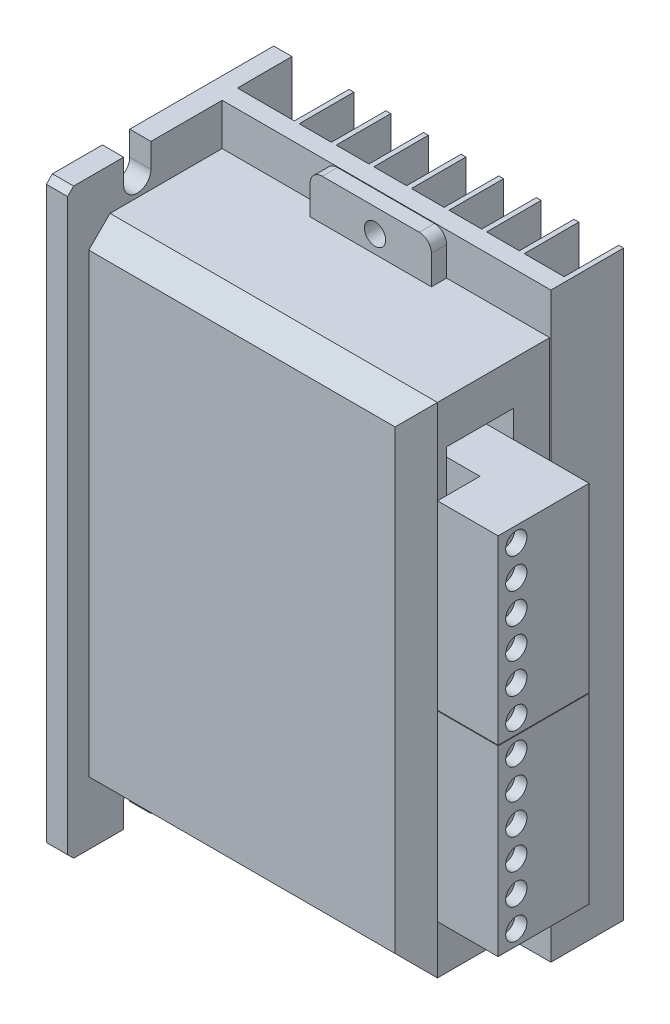
SolidWorks part; units mm, degrees
material "1060 Сплав"
ref_plane "Спереди" through (0, 0, 0) normal (0, 0, 1) x (1, 0, 0)
ref_plane "Сверху" through (0, 0, 0) normal (0, 1, 0) x (1, 0, 0)
ref_plane "Справа" through (0, 0, 0) normal (1, 0, 0) x (0, 0, -1)
sketch "Эскиз1" plane through (0, 0, 0) normal (0, 0, 1) x (1, 0, 0)
  line L0 (0, 0) -> (-27, 0) construction
  line L1 (-27, -41.1) -> (27, -41.1)
  line L2 (-27, -41.1) -> (-27, 41.1)
  line L3 (-27, 41.1) -> (27, 41.1)
  line L4 (27, -41.1) -> (27, 41.1)
  line L5 (-27, -41.1) -> (27, 41.1) construction
  line L6 (-27, 41.1) -> (27, -41.1) construction
  point P0 (0, 0)
  dimension "D1" = 82.2
  dimension "D2" = 54
extrude "Бобышка-Вытянуть1" add sketch "Эскиз1" along normal blind 22
chamfer "Фаска1" distance 3.5 angle 45 3 edges at (0, -41.1, 22) (27, 0, 22) (0, 41.1, 22)
sketch "Эскиз2" plane through (0, 0, 0) normal (0, 0, -1) x (-1, 0, 0)
  line L1 (-27.2, -48) -> (27, -48)
  line L2 (-27.2, -48) -> (-27.2, 48)
  line L3 (-27.2, 48) -> (27, 48)
  line L4 (27, -48) -> (27, 48)
  line L5 (27, 41.1) -> (27, -41.1) construction
  line L6 (27, 0) -> (0, 0) construction
  dimension "D1" = 96
  dimension "D3" = 54.2
extrude "Бобышка-Вытянуть2" add sketch "Эскиз2" along normal blind 12
sketch "Эскиз3" plane through (-27, 0, 0) normal (-1, 0, 0) x (0, 0, 1)
  line L1 (-12, 48) -> (11.75, 48)
  line L2 (-12, 48) -> (-12, -48)
  line L3 (-12, -48) -> (11.75, -48)
  line L4 (25.5, 48) -> (25.5, -48)
  line L6 (22, 37.6) -> (22, -37.6) construction
  line L7 (14, 59) -> (14, -59) construction
  line L8 (-12, 0) -> (25.5, 0) construction
  line L9 (11.75, 44) -> (11.75, 48)
  line L10 (16.25, 44) -> (16.25, 48)
  line L11 (16.25, 48) -> (25.5, 48)
  line L12 (16.25, -44) -> (16.25, -48)
  line L13 (11.75, -44) -> (11.75, -48)
  line L14 (16.25, -48) -> (25.5, -48)
  arc A0 (11.75, 44) -> (16.25, 44) centre (14, 44) ccw
  arc A1 (11.75, -44) -> (16.25, -44) centre (14, -44) cw
  dimension "D3" = 4.5
  dimension "D4" = 44
  dimension "D1" = 3.5
  dimension "D2" = 11.5
extrude "Бобышка-Вытянуть3" add sketch "Эскиз3" along normal blind 3.5
chamfer "Фаска2" distance 1 angle 45 2 edges at (-28.75, -48, 25.5) (-28.75, 48, 25.5)
sketch "Эскиз5" plane through (0, 0, -12) normal (0, 0, -1) x (-1, 0, 0)
  line L0 (30.5, 48) -> (-27.2, 48) construction
  line L1 (27.5, 48) -> (18.1, 48)
  line L2 (27.5, 48) -> (27.5, -48)
  line L3 (27.5, -48) -> (18.1, -48)
  line L4 (18.1, 48) -> (18.1, -48)
  line L5 (-27.2, -48) -> (30.5, -48) construction
  line L6 (30.5, 48) -> (30.5, -48) construction
  line L9 (17.3, 48) -> (17.3, -48)
  line L11 (12, 48) -> (12, -48)
  line L70 (17.3, 48) -> (12, 48)
  line L76 (12, -48) -> (17.3, -48)
  line L77 (11.2, 48) -> (11.2, -48)
  line L78 (5.8, 48) -> (5.8, -48)
  line L79 (5.8, 48) -> (11.2, 48)
  line L81 (5.8, 48) -> (5.8, -48)
  line L83 (5, 48) -> (5, -48)
  line L84 (5.8, -48) -> (11.2, -48)
  line L85 (-0.4, 48) -> (-0.4, -48)
  line L86 (5, 48) -> (5, -48)
  line L87 (-0.4, -48) -> (5, -48)
  line L88 (5.8, 48) -> (5.8, -48)
  line L89 (-6.6, 48) -> (-6.6, -48)
  line L90 (-1.2, 48) -> (-1.2, -48)
  line L91 (-6.6, -48) -> (-1.2, -48)
  line L92 (-0.4, 48) -> (-0.4, -48)
  line L93 (-12.8, 48) -> (-12.8, -48)
  line L94 (-7.4, 48) -> (-7.4, -48)
  line L95 (-12.8, -48) -> (-7.4, -48)
  line L96 (-6.6, 48) -> (-6.6, -48)
  line L97 (-19, 48) -> (-19, -48)
  line L98 (-13.6, 48) -> (-13.6, -48)
  line L99 (-19, -48) -> (-13.6, -48)
  line L100 (-12.8, 48) -> (-12.8, -48)
  line L102 (-19.8, 48) -> (-19.8, -48)
  line L103 (-25.2, -48) -> (-19.8, -48)
  line L104 (-19, 48) -> (-19, -48)
  line L105 (5, 48) -> (-0.4, 48)
  line L106 (-1.2, 48) -> (-6.6, 48)
  line L107 (-7.4, 48) -> (-12.8, 48)
  line L108 (-13.6, 48) -> (-19, 48)
  line L109 (-19.8, 48) -> (-25.2, 48)
  line L110 (5, 48) -> (-0.4, 48)
  line L111 (5.8, -48) -> (11.2, -48)
  line L112 (5, -48) -> (-0.4, -48)
  line L113 (-25.2, 48) -> (-26.3933, 48)
  line L114 (-25.2, 48) -> (-25.2, -48) [skipped]
  line L115 (-26.3933, 48) -> (-26.3933, -48)
  line L116 (-26.3933, -48) -> (-25.2, -48)
  line L117 (-27.2, 48) -> (-27.2, -48) construction
  line L119 (-0.4, 48) -> (5, 48)
  line L120 (-0.4, 48) -> (-0.4, -48)
  line L121 (-0.4, -48) -> (5, -48)
  line L122 (5, 48) -> (5, -48)
  line L123 (5.8, 48) -> (11.2, 48)
  line L124 (5.8, 48) -> (5.8, -48)
  line L125 (5.8, -48) -> (11.2, -48)
  line L126 (11.2, 48) -> (11.2, -48)
  dimension "D1" = 3
  dimension "D2" = 9.4
  dimension "D3" = 0.8
  dimension "D4" = 5.3
  dimension "D5" = 0.8
  dimension "D7" = 0.8
  dimension "D10" = 0.8067
  dimension "D8" = 6
extrude "Вырез-Вытянуть2" cut sketch "Эскиз5" against normal blind 9
sketch "Эскиз6" plane through (27, 0, 0) normal (1, 0, 0) x (0, 0, -1)
  line L0 (-6, 0) -> (-22, 0) construction
  line L2 (-22, 37.6) -> (-22, -37.6) construction
  line L4 (-6, 34) -> (-17, 34)
  line L5 (-6, 34) -> (-6, -34)
  line L6 (-6, -34) -> (-17, -34)
  line L7 (-17, 34) -> (-17, -34)
  line L8 (-6, 34) -> (-17, -34) construction
  line L9 (-6, -34) -> (-17, 34) construction
  point P6 (-11.5, 0)
  point P11 (12, 0)
  dimension "D1" = 11
  dimension "D2" = 5
  dimension "D3" = 68
extrude "Вырез-Вытянуть3" cut sketch "Эскиз6" against normal blind 7
sketch "Эскиз7" plane through (20, 0, 0) normal (1, 0, 0) x (0, 0, -1)
  line L0 (-11.5, -34) -> (-11.5, 34) construction
  line L1 (-17, -34) -> (-6, -34) construction
  line L2 (-6, 34) -> (-17, 34) construction
  line L3 (-6, -34) -> (-6, 34) construction
  line L4 (-6.5, -0.05) -> (-14.5, -0.05)
  line L5 (-6.5, -0.05) -> (-6.5, -30.05)
  line L6 (-6.5, -30.05) -> (-14.5, -30.05)
  line L7 (-14.5, -0.05) -> (-14.5, -30.05)
  line L8 (-6.5, -0.05) -> (-14.5, -30.05) construction
  line L9 (-6.5, -30.05) -> (-14.5, -0.05) construction
  line L12 (-6.5, 30.05) -> (-14.5, 30.05)
  line L13 (-6.5, 30.05) -> (-6.5, 0.05)
  line L14 (-6.5, 0.05) -> (-14.5, 0.05)
  line L15 (-14.5, 30.05) -> (-14.5, 0.05)
  line L16 (-6.5, 30.05) -> (-14.5, 0.05) construction
  line L17 (-6.5, 0.05) -> (-14.5, 30.05) construction
  line L18 (-14.5, 0.05) -> (-14.5, -0.05) construction
  line L19 (-14.5, 0) -> (-25.5, 0) construction
  line L20 (-25.5, -47) -> (-25.5, 47) construction
  point P6 (-10.5, -15.05)
  point P15 (-10.5, 15.05)
  point P20 (-10.5, -0.05)
  point P26 (-14.5, -13.4847)
  dimension "D1" = 0.5
  dimension "D2" = 30
  dimension "D4" = 8
  dimension "D5" = 0.5
  dimension "D6" = 0.1
  dimension "D7" = 30
  dimension "D8" = 8
extrude "Бобышка-Вытянуть5" add sketch "Эскиз7" along normal blind 10
sketch "Эскиз8" plane through (30, 0, 0) normal (1, 0, 0) x (0, 0, -1)
  line L1 (-6.5, -30.05) -> (-21.5, -30.05)
  line L2 (-6.5, -30.05) -> (-6.5, 0.0469)
  line L3 (-6.5, 0.0469) -> (-21.5, 0.0469)
  line L4 (-21.5, -30.05) -> (-21.5, 0.0469)
  line L5 (-6.5, 30.05) -> (-21.5, 30.05)
  line L6 (-6.5, 30.05) -> (-6.5, 0.1497)
  line L7 (-6.5, 0.1497) -> (-21.5, 0.1497)
  line L8 (-21.5, 30.05) -> (-21.5, 0.1497)
  point P11 (-18.9394, 0.2333)
  point P12 (-21.4136, 0.3933)
  dimension "D1" = 15
  dimension "D2" = 15
extrude "Бобышка-Вытянуть6" add sketch "Эскиз8" along normal blind 10
sketch "Эскиз9" plane through (40, 0, 0) normal (1, 0, 0) x (0, 0, -1)
  line L0 (-18.5, -30.05) -> (-18.5, 0.0469) construction
  line L1 (-21.5, -30.05) -> (-6.5, -30.05) construction
  line L2 (-6.5, 0.0469) -> (-21.5, 0.0469) construction
  line L3 (-21.5, 0.0469) -> (-21.5, -30.05) construction
  line L4 (-18.5, 0.1497) -> (-18.5, 30.05) construction
  line L5 (-21.5, 0.1497) -> (-6.5, 0.1497) construction
  line L6 (-6.5, 30.05) -> (-21.5, 30.05) construction
  line L8 (-21.5, 30.05) -> (-21.5, 0.1497) construction
  circle A0 centre (-18.5, -27.55) radius 1.75
  circle A1 centre (-18.5, -22.55) radius 1.75
  circle A2 centre (-18.5, -17.55) radius 1.75
  circle A3 centre (-18.5, -12.55) radius 1.75
  circle A4 centre (-18.5, -7.55) radius 1.75
  circle A5 centre (-18.5, -2.55) radius 1.75
  circle A6 centre (-18.5, 2.55) radius 1.75
  circle A7 centre (-18.5, 7.55) radius 1.75
  circle A8 centre (-18.5, 12.55) radius 1.75
  circle A9 centre (-18.5, 17.55) radius 1.75
  circle A10 centre (-18.5, 22.55) radius 1.75
  circle A11 centre (-18.5, 27.55) radius 1.75
  dimension "D1" = 3.5
  dimension "D3" = 2.5
  dimension "D5" = 2.5
  dimension "D6" = 3
  dimension "D8" = 3.5
  dimension "D4" = 3
  dimension "D2" = 6
  dimension "D7" = 6
extrude "Вырез-Вытянуть4" cut sketch "Эскиз9" against normal blind 2
sketch "Эскиз10" plane through (0, 41.1, 0) normal (0, 1, 0) x (1, 0, 0)
  line L0 (27, 0) -> (-27, 0) construction
  line L1 (-10, 0) -> (10, 0)
  line L2 (-10, 0) -> (-10, -2.5)
  line L3 (-10, -2.5) -> (10, -2.5)
  line L10 (10, 0) -> (10, -2.5)
  line L11 (27, -18.5) -> (27, 0) construction
  dimension "D1" = 17
  dimension "D2" = 20
  dimension "D3" = 2.5
extrude "Бобышка-Вытянуть7" add sketch "Эскиз10" along normal blind 6.8 contours L3 L10 L1 L2
sketch "Эскиз4" plane through (0, 0, 0) normal (0, 0, 1) x (1, 0, 0)
  line L0 (27.2, 48) -> (27.2, -48) construction
  line L1 (0.7, -44) -> (-12, -44) construction
  line L2 (36, 0) -> (-36, 0) construction
  circle A0 centre (0.7, -44) radius 1.75
  circle A2 centre (0.7, 44) radius 1.75
  point P12 (0, 0)
  dimension "D1" = 3.5
  dimension "D2" = 44
  dimension "D3" = 26.5
extrude "Вырез-Вытянуть1" cut sketch "Эскиз4" against normal blind 7 and the other way through all from offset 2
fillet "Скругление1" radius 2 2 edges at (10, 47.9, 1.25) (-10, 47.9, 1.25)
mirror "Зеркальное отражение1" about plane through (0, 0, 0) normal (0, 1, 0) of "Вырез-Вытянуть1", "Скругление1", "Бобышка-Вытянуть7"
